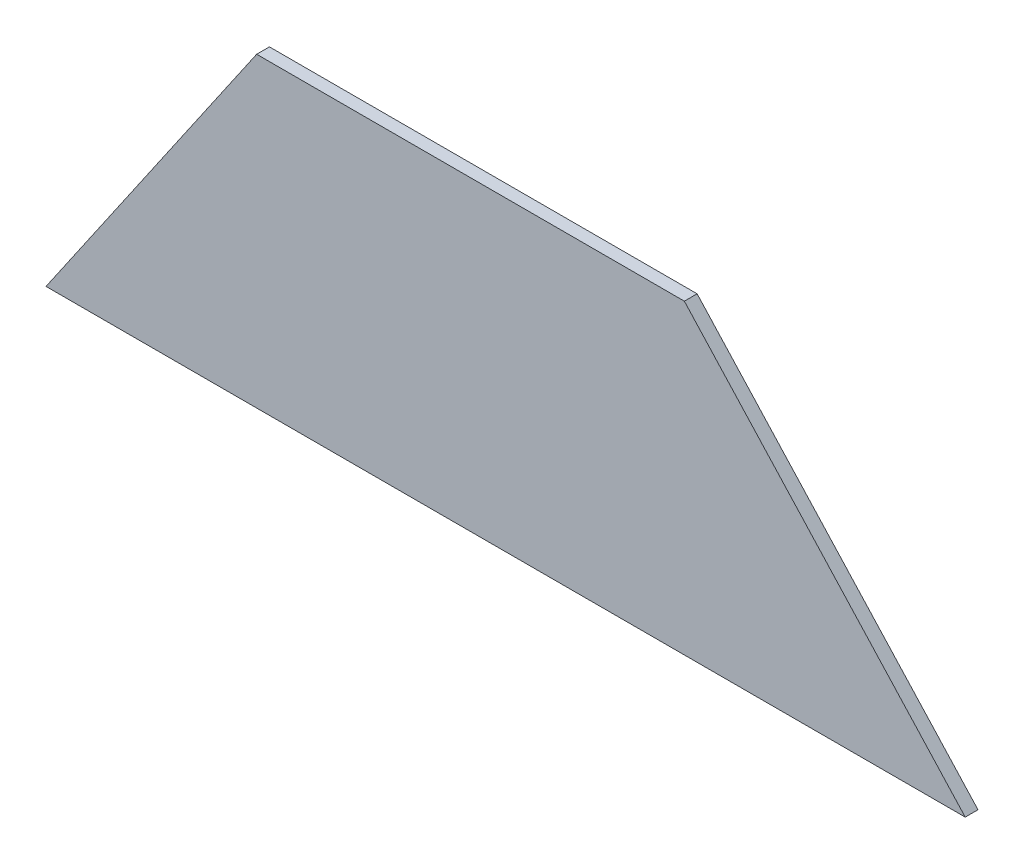
SolidWorks part; units mm, degrees
material "Magnesium Alloy"
ref_plane "Front Plane" through (0, 0, 0) normal (0, 0, 1) x (1, 0, 0)
ref_plane "Top Plane" through (0, 0, 0) normal (0, 1, 0) x (1, 0, 0)
ref_plane "Right Plane" through (0, 0, 0) normal (1, 0, 0) x (0, 0, -1)
sketch "Sketch2" plane through (0, 0, 0) normal (0, 0, 1) x (1, 0, 0)
  line L0 (0, 0) -> (114.3, 0)
  line L1 (114.3, 0) -> (79.375, 38.1)
  line L2 (79.375, 38.1) -> (26.1937, 38.1)
  line L3 (26.1937, 38.1) -> (0, 0)
  dimension "D1" = 38.1
  dimension "D2" = 114.3
  dimension "D3" = 53.1812
  dimension "D4" = 34.925
extrude "Boss-Extrude1" add sketch "Sketch2" along normal blind 1.5875
